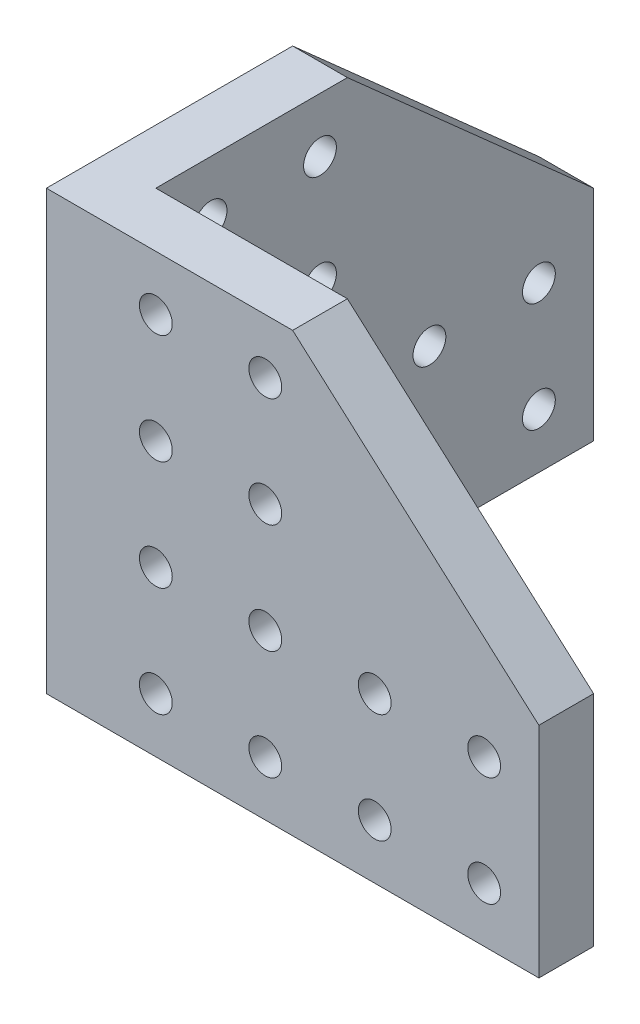
SolidWorks part; units mm, degrees
ref_plane "Front Plane" through (0, 0, 0) normal (0, 0, 1) x (1, 0, 0)
ref_plane "Top Plane" through (0, 0, 0) normal (0, 1, 0) x (1, 0, 0)
ref_plane "Right Plane" through (0, 0, 0) normal (1, 0, 0) x (0, 0, -1)
sketch "Sketch1" plane through (0, 0, 0) normal (0, 1, 0) x (1, 0, 0)
  line L0 (0, 0) -> (90, 0)
  line L1 (90, 0) -> (90, 10)
  line L2 (90, 10) -> (10, 10)
  line L3 (10, 10) -> (10, 90)
  line L4 (10, 90) -> (0, 90)
  line L5 (0, 90) -> (0, 0)
  dimension "D1" = 90
  dimension "D2" = 90
  dimension "D3" = 10
  dimension "D4" = 10
extrude "Boss-Extrude1" add sketch "Sketch1" along normal blind 80
sketch "Sketch2" plane through (0, 0, 0) normal (0, 0, 1) x (1, 0, 0)
  line L0 (45, 80) -> (90, 40)
  line L1 (0, 80) -> (90, 80) construction
  line L2 (90, 80) -> (90, 0) construction
  line L3 (90, 40) -> (90, 80)
  line L4 (90, 80) -> (45, 80)
extrude "Cut-Extrude1" cut sketch "Sketch2" against normal up to next
sketch "Sketch3" plane through (0, 0, 0) normal (-1, 0, 0) x (0, 0, 1)
  line L0 (-45, 80) -> (-90, 40)
  line L1 (-90, 80) -> (0, 80) construction
  line L2 (-90, 80) -> (-90, 0) construction
  line L3 (-90, 40) -> (-90, 80)
  line L4 (-90, 80) -> (-45, 80)
extrude "Cut-Extrude2" cut sketch "Sketch3" against normal up to next
sketch "Sketch4" plane through (0, 0, 0) normal (0, 0, 1) x (1, 0, 0)
  line L0 (0, 0) -> (90, 0) construction
  line L1 (0, 80) -> (45, 80) construction
  line L2 (0, 80) -> (0, 0) construction
  line L3 (90, 40) -> (90, 0) construction
  circle A0 centre (20, 70) radius 3
  circle A1 centre (40, 70) radius 3
  circle A2 centre (40, 50) radius 3
  circle A3 centre (20, 30) radius 3
  circle A4 centre (40, 10) radius 3
  circle A5 centre (20, 50) radius 3
  circle A6 centre (40, 30) radius 3
  circle A7 centre (20, 10) radius 3
  circle A8 centre (60, 30) radius 3
  circle A9 centre (80, 10) radius 3
  circle A10 centre (80, 30) radius 3
  circle A11 centre (60, 10) radius 3
  dimension "D1" = 6
  dimension "D2" = 10
  dimension "D3" = 20
  dimension "D4" = 10
  dimension "D5" = 20
  dimension "D6" = 20
  dimension "D7" = 20
  dimension "D8" = 20
  dimension "D9" = 10
extrude "Cut-Extrude3" cut sketch "Sketch4" against normal up to next
sketch "Sketch5" plane through (0, 0, 0) normal (-1, 0, 0) x (0, 0, 1)
  line L0 (-45, 80) -> (0, 80) construction
  line L1 (-90, 0) -> (0, 0) construction
  line L2 (0, 80) -> (0, 0) construction
  line L3 (-90, 40) -> (-90, 0) construction
  circle A0 centre (-20, 30) radius 2.5
  circle A1 centre (-40, 30) radius 2.5
  circle A2 centre (-40, 10) radius 2.5
  circle A3 centre (-20, 10) radius 2.5
  circle A5 centre (-20, 70) radius 3
  circle A6 centre (-40, 70) radius 3
  circle A7 centre (-40, 50) radius 3
  circle A8 centre (-20, 50) radius 3
  circle A9 centre (-60, 30) radius 3
  circle A10 centre (-80, 30) radius 3
  circle A11 centre (-80, 10) radius 3
  circle A12 centre (-60, 10) radius 3
  dimension "D1" = 5
  dimension "D2" = 6
  dimension "D3" = 10
  dimension "D4" = 20
  dimension "D5" = 20
  dimension "D6" = 10
  dimension "D7" = 20
  dimension "D8" = 20
  dimension "D9" = 20
  dimension "D10" = 10
extrude "Cut-Extrude4" cut sketch "Sketch5" against normal up to next
